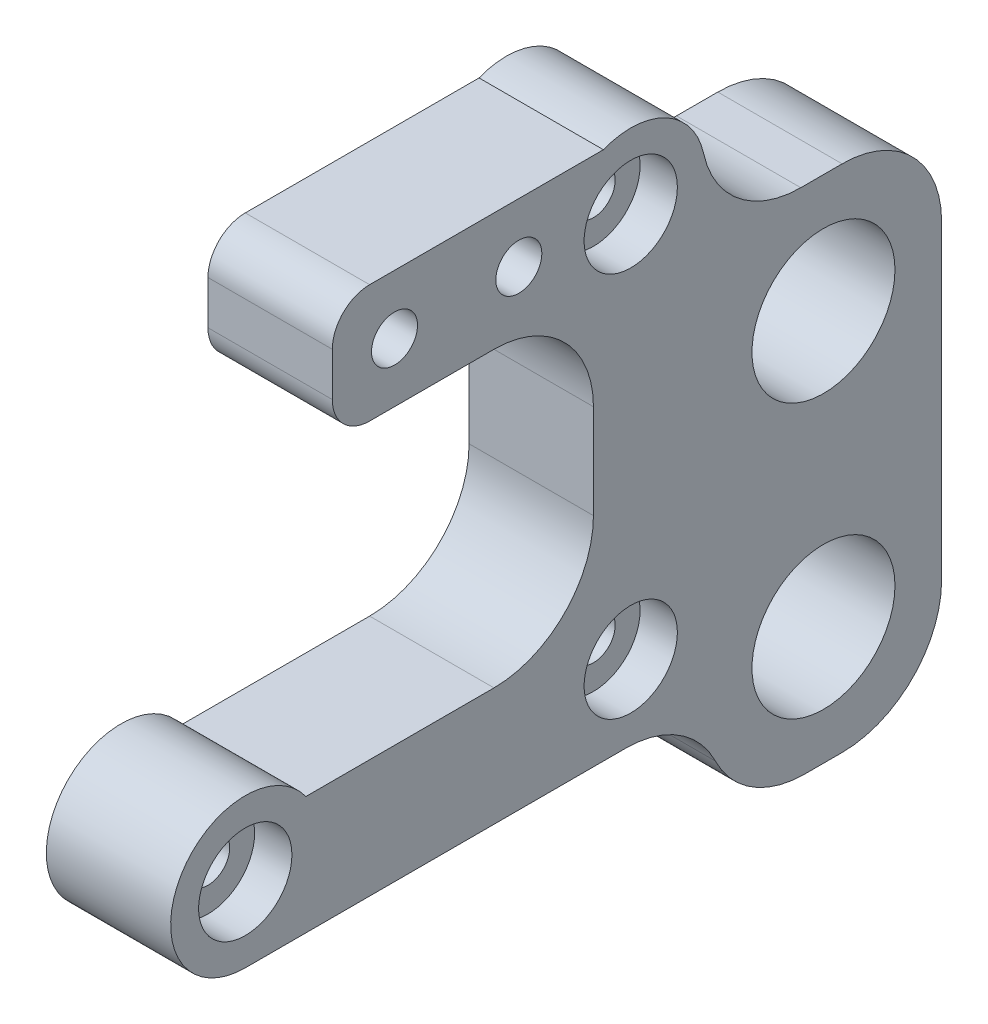
SolidWorks part; units mm, degrees
ref_plane "Front Plane" through (0, 0, 0) normal (0, 0, 1) x (1, 0, 0)
ref_plane "Top Plane" through (0, 0, 0) normal (0, 1, 0) x (1, 0, 0)
ref_plane "Right Plane" through (0, 0, 0) normal (1, 0, 0) x (0, 0, -1)
ref_plane "Plane1" through (20, 0, 0) normal (1, 0, 0) x (0, 0, -1)
sketch "Sketch1" plane through (20, 0, 0) normal (1, 0, 0) x (0, 0, -1)
  line L0 (-17.6996, 42.0822) -> (-39.4998, 42.0822)
  line L1 (-18.4998, 32.5822) -> (-18.4998, 9)
  line L2 (-18.4998, 9) -> (-41.6264, 9)
  line L3 (-46.4998, -0.5) -> (-9.4998, -0.5)
  line L4 (-39.4998, 42.0822) -> (-39.4998, 32.5822)
  line L5 (-9.4998, 36.5) -> (-9.4998, 31.5)
  line L6 (-39.4998, 32.5822) -> (-18.4998, 32.5822)
  line L7 (-9.4998, 31.5) -> (-9.4998, -0.5) construction
  line L8 (9.5002, 31.5) -> (9.5002, -9.5)
  line L9 (9.5002, -9.5) -> (-9.4998, -9.5)
  line L10 (-9.4998, -0.5) -> (-9.4998, -9.5)
  line L13 (-9.4998, 31.5) -> (9.5002, 31.5)
  arc A0 (-41.6264, 9) -> (-46.4998, -0.5) centre (-46.4998, 5.5) ccw
  arc A1 (-9.4998, 36.5) -> (-17.6996, 42.0822) centre (-15.4998, 36.5) ccw
  circle A4 centre (-15.4998, 36.5) radius 1.75
  circle A5 centre (0.0002, 22) radius 5.75
  circle A6 centre (0.0002, 0) radius 5.75
  circle A7 centre (-15.4998, 5.5) radius 1.75
  circle A8 centre (-46.4998, 5.5) radius 1.75
  dimension "D6" = 30
  dimension "D10" = 11.5
  dimension "D18" = 6
  dimension "D19" = 3.5
  dimension "D2" = 31
  dimension "D3" = 31
  dimension "D4" = 41
  dimension "D5" = 9.5
  dimension "D11" = 22
  dimension "D12" = 9.5
  dimension "D13" = 19
  dimension "D14" = 9.5
  dimension "D15" = 9
  dimension "D16" = 9.5
  dimension "D17" = 9
extrude "Boss-Extrude3" add sketch "Sketch1" along normal blind 10
fillet "Fillet1" radius 8 6 edges at (25, -9.5, 9.4998) (25, -9.5, -9.5002) (25, 31.5, -9.5002) (25, 9, 18.4998) (25, 31.5, 9.4998) (25, 32.5822, 18.4998)
sketch "Sketch6" plane through (30, 0, 0) normal (1, 0, 0) x (0, 0, -1)
  circle A0 centre (-15.4998, 36.5) radius 3.75
  circle A1 centre (-15.4998, 5.5) radius 3.75
  circle A2 centre (-46.4998, 5.5) radius 3.75
  dimension "D1" = 7.5
extrude "Cut-Extrude2" cut sketch "Sketch6" against normal blind 3
fillet "Fillet2" radius 8 1 edges at (25, -0.5, 9.4998)
fillet "Fillet3" radius 3 2 edges at (25, 32.5822, 39.4998) (25, 42.0822, 39.4998)
sketch "Sketch8" plane through (30, 0, 0) normal (1, 0, 0) x (0, 0, -1)
  line L2 (-36.4998, 32.5822) -> (-26.4998, 32.5822) construction
  line L3 (-39.4998, 39.0822) -> (-39.4998, 35.5822) construction
  circle A0 centre (-34.4998, 37.3322) radius 1.85
  circle A1 centre (-24.4998, 37.3322) radius 1.85
  dimension "D2" = 3.7
  dimension "D1" = 10
  dimension "D3" = 4.75
  dimension "D4" = 5
extrude "Cut-Extrude3" cut sketch "Sketch8" against normal through all contours A0
sketch "Sketch9" plane through (20, 0, 0) normal (-1, 0, 0) x (0, 0, 1)
  circle A0 centre (24.4998, 37.3322) radius 3.75
  circle A1 centre (34.4998, 37.3322) radius 3.75
extrude "Cut-Extrude4" cut sketch "Sketch9" against normal blind 4
